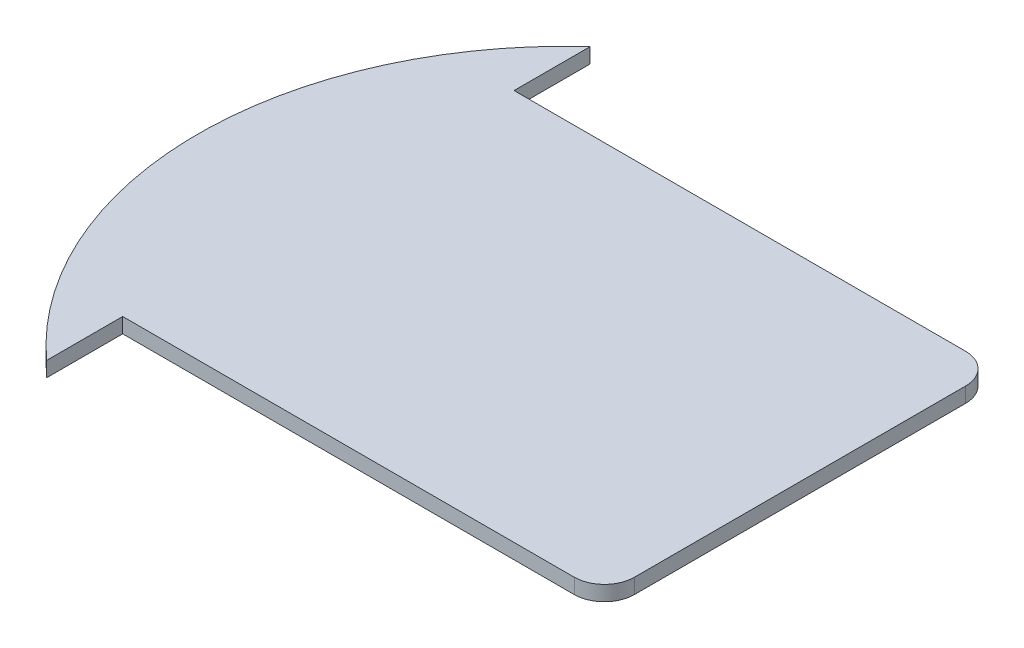
SolidWorks part; units mm, degrees
ref_plane "Front Plane" through (0, 0, 0) normal (0, 0, 1) x (1, 0, 0)
ref_plane "Top Plane" through (0, 0, 0) normal (0, 1, 0) x (1, 0, 0)
ref_plane "Right Plane" through (0, 0, 0) normal (1, 0, 0) x (0, 0, -1)
sketch "Sketch1" plane through (0, 0, 0) normal (0, 1, 0) x (1, 0, 0)
  line L0 (40.3018, 25) -> (110.3018, 25)
  line L4 (200.3018, 25) -> (200.3018, 155)
  line L6 (40.3018, 180.2747) -> (40.3018, 155)
  line L7 (40.3018, 155) -> (110.3018, 155)
  line L9 (40.3018, 25) -> (40.3018, -0.2747)
  line L12 (110.3018, 25) -> (200.3018, 25)
  line L13 (110.3018, 155) -> (200.3018, 155)
  arc A0 (40.3018, 180.2747) -> (40.3018, -0.2747) centre (122.1708, 90) ccw
  point P0 (0.3018, 90)
  dimension "D1" = 160
  dimension "D2" = 200
extrude "Boss-Extrude1" add sketch "Sketch1" along normal blind 5
fillet "Fillet1" radius 10 2 edges at (200.3018, 2.5, -155) (200.3018, 2.5, -25)
ref_plane "Plane1" through (0, 0, -90) normal (0, 0, 1) x (1, 0, 0)
